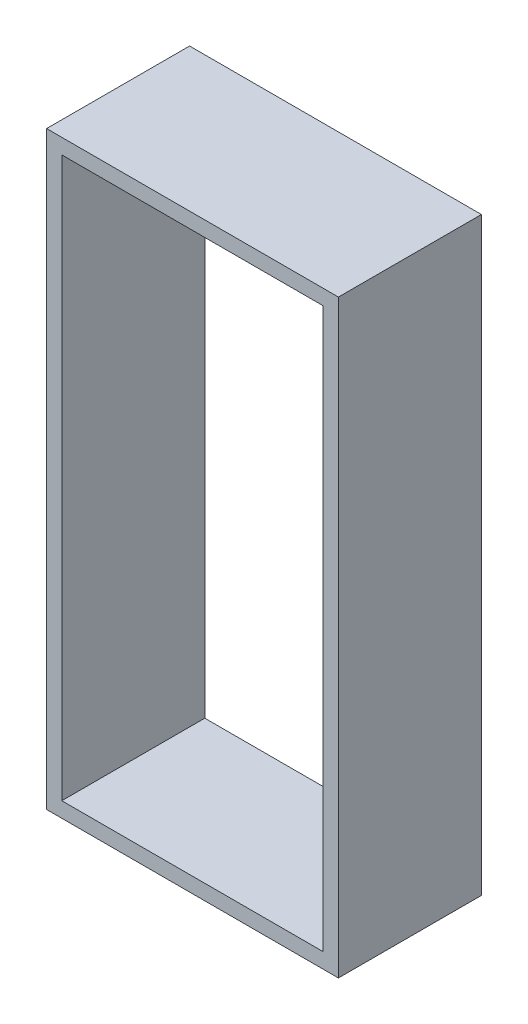
SolidWorks part; units mm, degrees
ref_plane "Front Plane" through (0, 0, 0) normal (0, 0, 1) x (1, 0, 0)
ref_plane "Top Plane" through (0, 0, 0) normal (0, 1, 0) x (1, 0, 0)
ref_plane "Right Plane" through (0, 0, 0) normal (1, 0, 0) x (0, 0, -1)
sketch "Sketch1" plane through (0, 0, 0) normal (0, 0, 1) x (1, 0, 0)
  line L0 (-3.175, 120.015) -> (57.785, 120.015)
  line L1 (0, 0) -> (54.61, 0)
  line L2 (0, 0) -> (0, 116.84)
  line L3 (0, 116.84) -> (54.61, 116.84)
  line L4 (54.61, 0) -> (54.61, 116.84)
  line L5 (57.785, -3.175) -> (57.785, 120.015)
  line L6 (-3.175, -3.175) -> (57.785, -3.175)
  line L7 (-3.175, -3.175) -> (-3.175, 120.015)
  point P14 (0, 58.42)
  point P16 (27.305, 116.84)
  point P17 (34.3412, 1.3555)
  point P20 (34.6208, 116.1305)
  point P21 (-114.6429, -10.9897)
  dimension "D1" = 54.61
  dimension "D2" = 116.84
  dimension "D3" = 3.175
extrude "Boss-Extrude1" add sketch "Sketch1" along normal blind 29.8704
